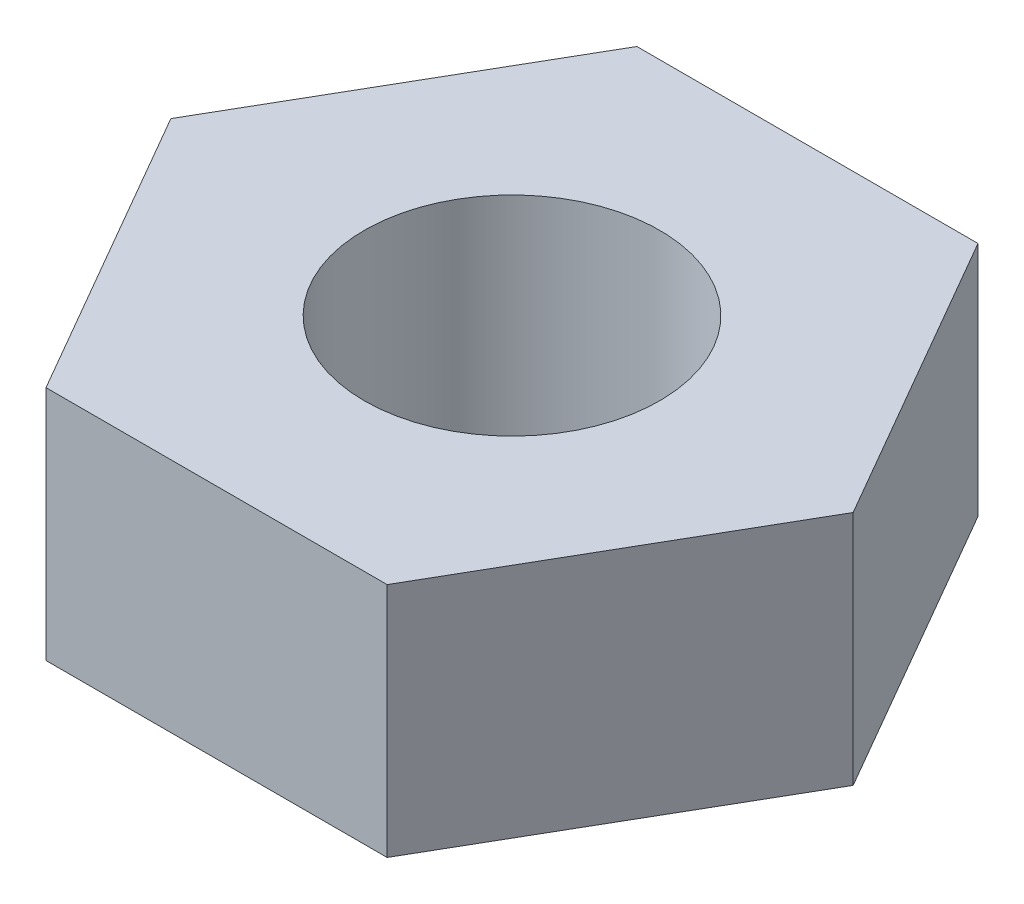
SolidWorks part; units mm, degrees
ref_plane "前视基准面" through (0, 0, 0) normal (0, 0, 1) x (1, 0, 0)
ref_plane "上视基准面" through (0, 0, 0) normal (0, 1, 0) x (1, 0, 0)
ref_plane "右视基准面" through (0, 0, 0) normal (1, 0, 0) x (0, 0, -1)
other "Configuration Table"
sketch "草图1" plane through (0, 0, 0) normal (0, 1, 0) x (1, 0, 0)
  line L1 (1.1547, -2) -> (2.3094, 0)
  line L2 (2.3094, 0) -> (1.1547, 2)
  line L3 (1.1547, 2) -> (-1.1547, 2)
  line L4 (-1.1547, 2) -> (-2.3094, 0)
  line L5 (-2.3094, 0) -> (-1.1547, -2)
  line L6 (-1.1547, -2) -> (1.1547, -2)
  circle A0 centre (0, 0) radius 1
  dimension "D1" = 2
  dimension "D2" = 4
extrude "凸台-拉伸1" add sketch "草图1" along normal blind 1.6
